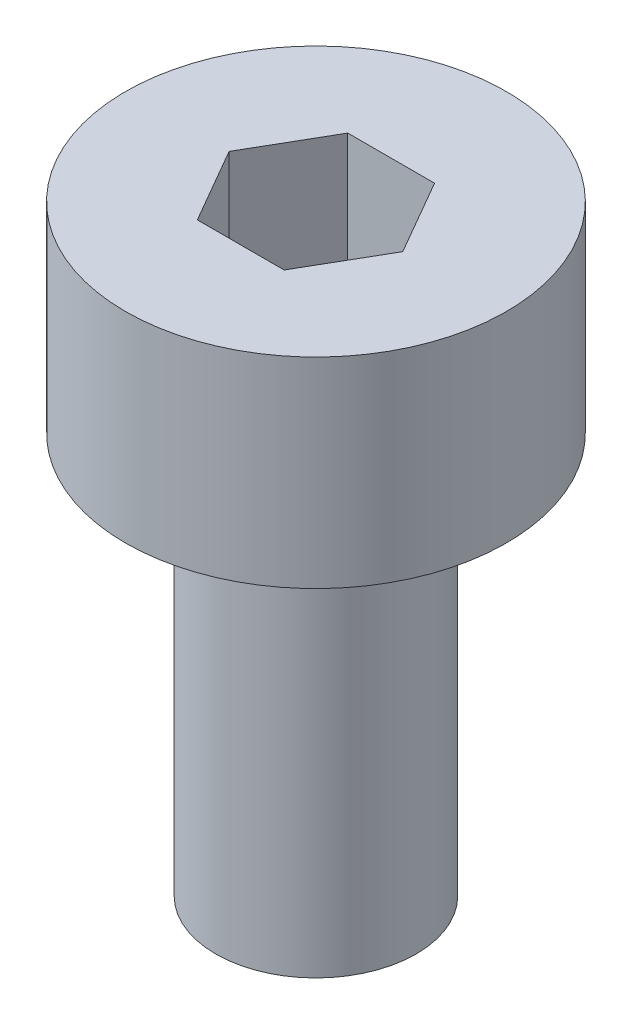
SolidWorks part; units mm, degrees
material "AISI 304"
ref_plane "Front Plane" through (0, 0, 0) normal (0, 0, 1) x (1, 0, 0)
ref_plane "Top Plane" through (0, 0, 0) normal (0, 1, 0) x (1, 0, 0)
ref_plane "Right Plane" through (0, 0, 0) normal (1, 0, 0) x (0, 0, -1)
sketch "Sketch1" plane through (0, 0, 0) normal (0, 0, 1) x (1, 0, 0)
  line L0 (0, 61.6916) -> (0, -59.3578) construction
  line L1 (0, -4) -> (1, -4)
  line L2 (1, -4) -> (1, 0)
  line L3 (1, 0) -> (1.9, 0)
  line L4 (1.9, 0) -> (1.9, 2)
  line L5 (1.9, 2) -> (0, 2)
  line L6 (0, 2) -> (0, -4)
  dimension "D1" = 4
  dimension "D2" = 3.8
  dimension "D3" = 2
  dimension "D4" = 2
revolve "Revolve1" add sketch "Sketch1" angle 360 about L0
sketch "Sketch2" plane through (0, 2, 0) normal (0, 1, 0) x (-1, 0, 0)
  line L1 (-0.433, -0.75) -> (0.433, -0.75)
  line L2 (0.433, -0.75) -> (0.866, 0)
  line L3 (0.866, 0) -> (0.433, 0.75)
  line L4 (0.433, 0.75) -> (-0.433, 0.75)
  line L5 (-0.433, 0.75) -> (-0.866, 0)
  line L6 (-0.866, 0) -> (-0.433, -0.75)
  circle A0 centre (0, 0) radius 0.75 construction
  dimension "D1" = 1.5
extrude "Cut-Extrude1" cut sketch "Sketch2" against normal blind 1.5
